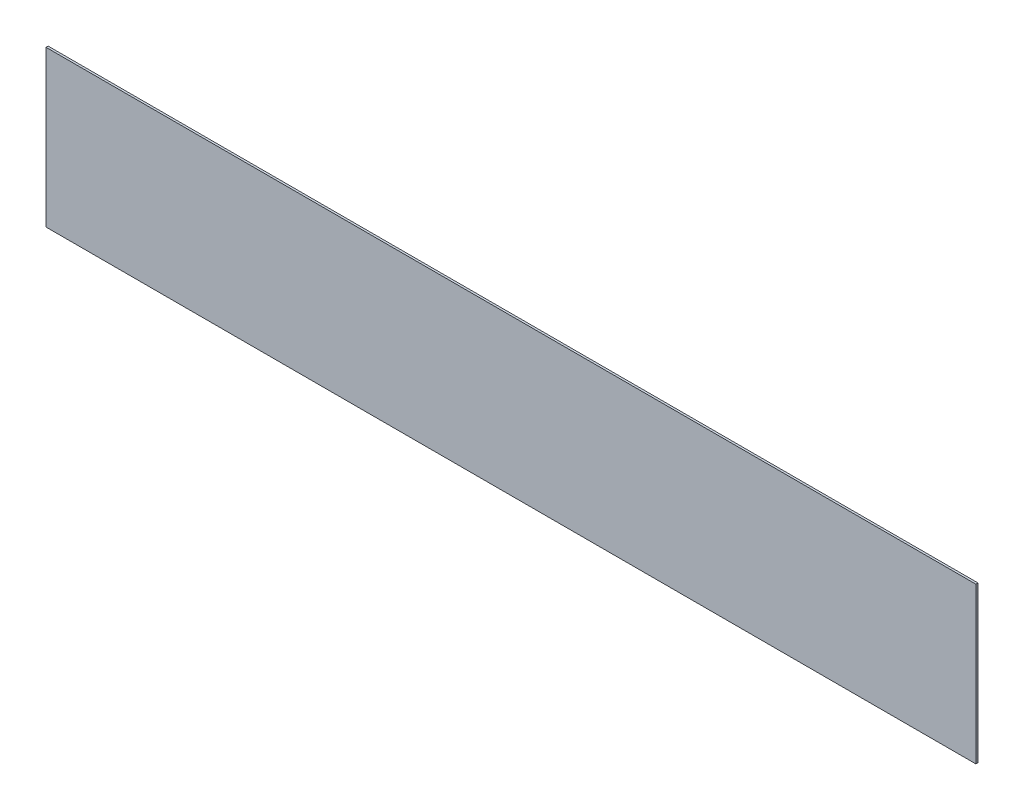
SolidWorks part; units mm, degrees
ref_plane "Front Plane" through (0, 0, 0) normal (0, 0, 1) x (1, 0, 0)
ref_plane "Top Plane" through (0, 0, 0) normal (0, 1, 0) x (1, 0, 0)
ref_plane "Right Plane" through (0, 0, 0) normal (1, 0, 0) x (0, 0, -1)
other "Configuration Table"
sketch "Sketch1" plane through (0, 0, 0) normal (0, 0, 1) x (1, 0, 0)
  line L1 (21.5, 10) -> (678.5, 10)
  line L2 (21.5, 10) -> (21.5, 120)
  line L3 (21.5, 120) -> (678.5, 120)
  line L4 (678.5, 10) -> (678.5, 120)
extrude "OVEN_plint_arka_1" add sketch "Sketch1" against normal blind 1.5 from offset 798.5 separate body
